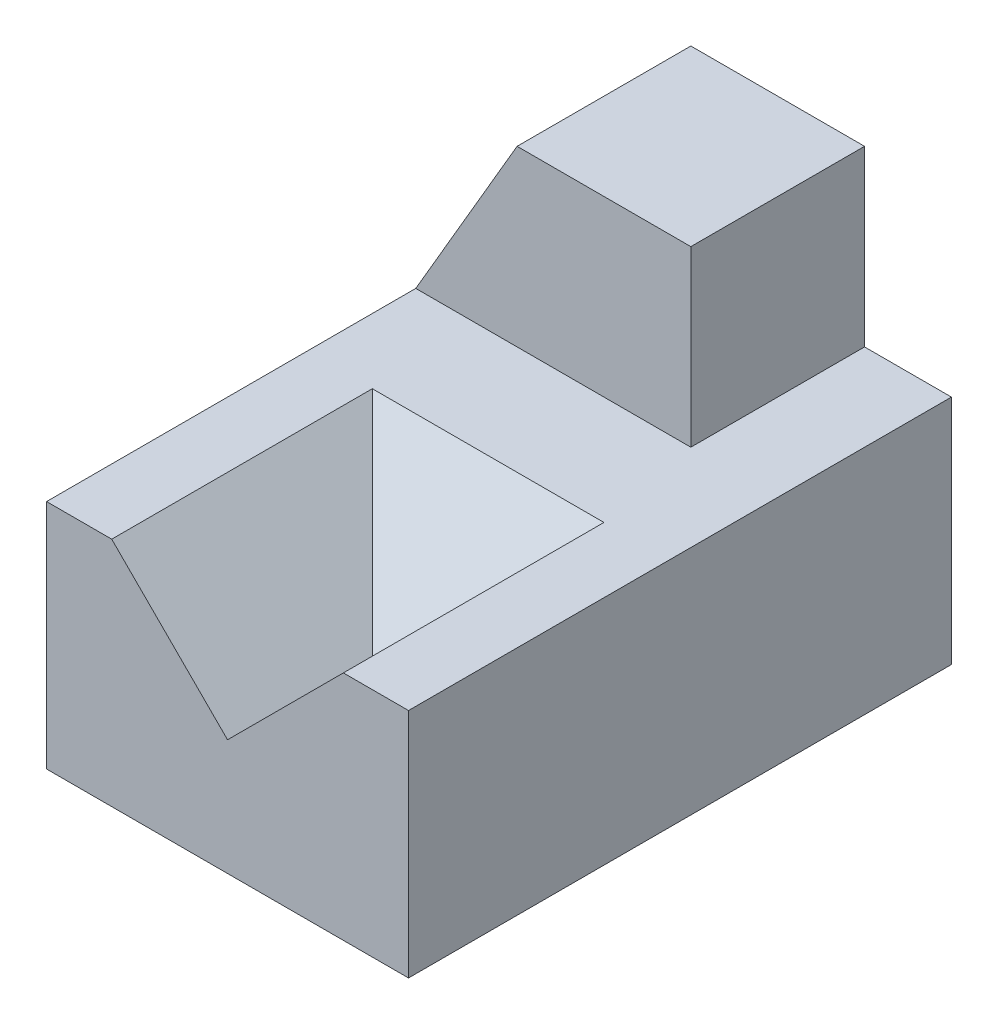
SolidWorks part; units mm, degrees
ref_plane "Front Plane" through (0, 0, 0) normal (0, 0, 1) x (1, 0, 0)
ref_plane "Top Plane" through (0, 0, 0) normal (0, 1, 0) x (1, 0, 0)
ref_plane "Right Plane" through (0, 0, 0) normal (1, 0, 0) x (0, 0, -1)
sketch "Sketch1" plane through (0, 0, 0) normal (0, 1, 0) x (1, 0, 0)
  line L1 (0, 0) -> (-50, 0)
  line L2 (0, 0) -> (0, 75)
  line L3 (0, 75) -> (-50, 75)
  line L4 (-50, 0) -> (-50, 75)
  dimension "D1" = 75
  dimension "D2" = 50
extrude "Boss-Extrude1" add sketch "Sketch1" along normal blind 32
ref_plane "Plane1" through (0, 32, 0) normal (0, 1, 0) x (1, 0, 0)
sketch "Sketch3" plane through (0, 32, 0) normal (0, 1, 0) x (1, 0, 0)
  line L0 (-41, 36) -> (-9, 36)
  line L1 (-9, 36) -> (-9, 0)
  line L2 (-50, 0) -> (0, 0) construction
  line L3 (-41, 36) -> (-41, 0)
  line L4 (-41, 0) -> (-9, 0)
  line L5 (0, 0) -> (0, 75) construction
  line L6 (-50, 75) -> (-50, 0) construction
  dimension "D1" = 9
  dimension "D2" = 9
  dimension "D3" = 36
extrude "Cut-Extrude1" cut sketch "Sketch3" against normal blind 16 draft 45
ref_plane "Plane2" through (0, 0, 0) normal (0, 0, 1) x (1, 0, 0)
sketch "Sketch4" plane through (0, 0, 0) normal (0, 0, 1) x (1, 0, 0)
  line L0 (-9, 32) -> (-25, 16)
  line L1 (-25, 16) -> (-41, 32)
  line L2 (-50, 32) -> (-50, 0) construction
  line L3 (-50, 0) -> (0, 0) construction
  line L4 (-41, 32) -> (-9, 32)
  dimension "D1" = 25
  dimension "D2" = 16
extrude "Cut-Extrude3" cut sketch "Sketch4" against normal blind 16
sketch "Sketch5" plane through (0, 32, 0) normal (0, 1, 0) x (1, 0, 0)
  line L0 (-50, 51) -> (-12, 51)
  line L1 (-50, 75) -> (-50, 0) construction
  line L2 (-12, 51) -> (-12, 75)
  line L3 (0, 75) -> (-50, 75) construction
  line L4 (0, 0) -> (0, 75) construction
  line L5 (-50, 75) -> (-50, 51)
  line L6 (-50, 75) -> (-12, 75)
  dimension "D1" = 12
  dimension "D2" = 24
ref_plane "Plane3" through (0, 0, -51) normal (0, 0, 1) x (1, 0, 0)
sketch "Sketch6" plane through (0, 0, -51) normal (0, 0, 1) x (1, 0, 0)
  line L0 (-12, 32) -> (-12, 56)
  line L1 (-50, 32) -> (-12, 32) construction
  line L2 (-12, 56) -> (-36, 56)
  line L3 (-36, 56) -> (-50, 32)
  line L4 (-50, 32) -> (-50, 0) construction
  line L5 (-50, 0) -> (0, 0) construction
  line L6 (-50, 32) -> (-12, 32)
  dimension "D1" = 24
  dimension "D2" = 12
  dimension "D3" = 56
extrude "Boss-Extrude2" add sketch "Sketch6" against normal blind 24
